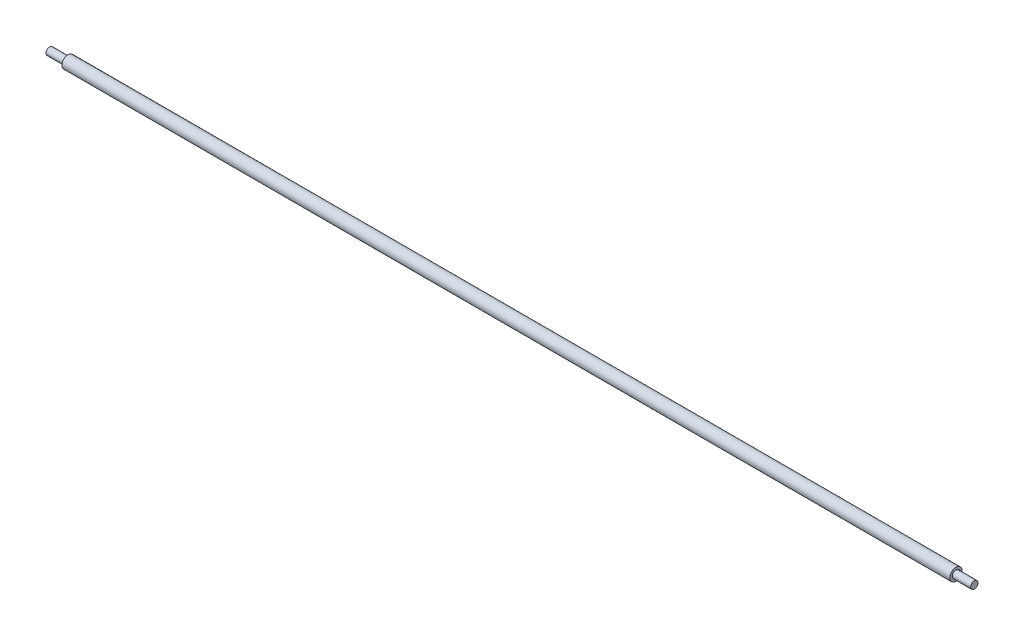
SolidWorks part; units mm, degrees
ref_plane "Спереди" through (0, 0, 0) normal (0, 0, 1) x (1, 0, 0)
ref_plane "Сверху" through (0, 0, 0) normal (0, 1, 0) x (1, 0, 0)
ref_plane "Справа" through (0, 0, 0) normal (1, 0, 0) x (0, 0, -1)
sketch "Эскиз1" plane through (0, 0, 0) normal (1, 0, 0) x (0, 0, -1)
  circle A0 centre (0, 0) radius 5
  dimension "D1" = 10
extrude "Бобышка-Вытянуть1" add sketch "Эскиз1" along normal blind 455 and the other way blind 270
sketch "Эскиз2" plane through (-270, 0, 0) normal (-1, 0, 0) x (0, 0, 1)
  circle A0 centre (0, 0) radius 3
  dimension "D1" = 6
extrude "Бобышка-Вытянуть2" add sketch "Эскиз2" along normal blind 15
cosmetic thread "Условное изображение резьбы4" parameters "D1"=14.9999, "D2"=4.891
sketch "Эскиз7" plane through (455, 0, 0) normal (1, 0, 0) x (0, 0, -1)
  circle A0 centre (0, 0) radius 3
  dimension "D1" = 6
extrude "Бобышка-Вытянуть3" add sketch "Эскиз7" along normal blind 15
cosmetic thread "Условное изображение резьбы5" parameters "D1"=14.9999, "D2"=4.891
